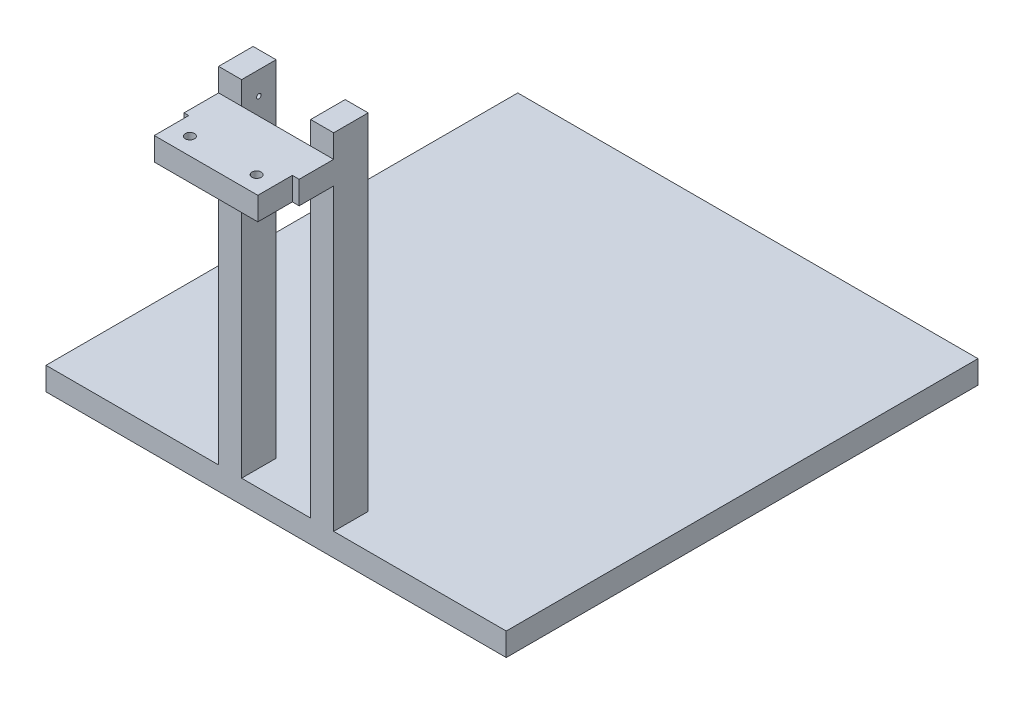
SolidWorks part; units mm, degrees
ref_plane "Front Plane" through (0, 0, 0) normal (0, 0, 1) x (1, 0, 0)
ref_plane "Top Plane" through (0, 0, 0) normal (0, 1, 0) x (1, 0, 0)
ref_plane "Right Plane" through (0, 0, 0) normal (1, 0, 0) x (0, 0, -1)
sketch "Sketch1" plane through (0, 0, 0) normal (0, 1, 0) x (1, 0, 0)
  line L1 (-100, 102.5) -> (100, 102.5)
  line L2 (-100, 102.5) -> (-100, -102.5)
  line L3 (-100, -102.5) -> (100, -102.5)
  line L4 (100, 102.5) -> (100, -102.5)
  line L5 (-100, 102.5) -> (100, -102.5) construction
  line L6 (-100, -102.5) -> (100, 102.5) construction
  point P0 (0, 0)
  dimension "D1" = 200
  dimension "D2" = 205
extrude "Boss-Extrude1" add sketch "Sketch1" along normal blind 10
sketch "Sketch2" plane through (0, 0, 0) normal (0, 1, 0) x (1, 0, 0)
  line L0 (0, -102.5) -> (0, 102.5)
  line L1 (-100, -102.5) -> (100, -102.5) construction
  line L2 (100, 102.5) -> (-100, 102.5) construction
  line L3 (0, 102.5) -> (66.3962, 67.7798)
  line L4 (-15, -102.5) -> (15, -102.5)
  line L5 (15, -102.5) -> (15, -87.5)
  line L6 (15, -87.5) -> (25, -87.5)
  line L7 (25, -87.5) -> (25, -102.5)
  line L8 (25, -102.5) -> (15, -102.5)
  line L9 (-15, -102.5) -> (-15, -87.5)
  line L10 (-15, -87.5) -> (-25, -87.5)
  line L11 (-25, -87.5) -> (-25, -102.5)
  line L12 (-25, -102.5) -> (-15, -102.5)
  line L13 (15, -102.5) -> (25, -102.5)
  line L14 (-25, -102.5) -> (-15, -102.5)
  point P10 (0, -102.5)
  dimension "D1" = 30
  dimension "D2" = 15
  dimension "D3" = 10
  dimension "D4" = 10
extrude "Boss-Extrude2" add sketch "Sketch2" along normal blind 160 contours L11 L12 L9 L10 | L8 L7 L6 L5
ref_plane "Plane1" through (0, 0, 102.5) normal (0, 0, 1) x (1, 0, 0)
sketch "Sketch4" plane through (0, 0, 102.5) normal (0, 0, 1) x (1, 0, 0)
  line L0 (-25, 160) -> (-25, 150)
  line L1 (-25, 160) -> (-25, 10) construction
  line L2 (-25, 150) -> (25, 150)
  line L3 (25, 160) -> (25, 10) construction
  line L4 (25, 150) -> (25, 160)
  line L5 (-25, 150) -> (25, 150)
  line L6 (-25, 150) -> (-25, 140)
  line L7 (-25, 140) -> (25, 140)
  line L8 (25, 140) -> (25, 150)
  point P13 (0, 150)
  dimension "D1" = 10
  dimension "D2" = 50
  dimension "D3" = 10
extrude "Boss-Extrude3" add sketch "Sketch4" along normal blind 15 contours L7 L8 L2 L6
ref_plane "Plane2" through (0, 0, 117.5) normal (0, 0, 1) x (1, 0, 0)
sketch "Sketch5" plane through (0, 0, 117.5) normal (0, 0, 1) x (1, 0, 0)
  line L0 (-22.9526, 150) -> (22.0474, 150)
  line L1 (-25, 150) -> (25, 150) construction
  line L2 (22.0474, 150) -> (22.0474, 140)
  line L3 (-25, 140) -> (25, 140) construction
  line L4 (22.0474, 140) -> (-22.9526, 140)
  line L5 (-22.9526, 140) -> (-22.9526, 150)
  point P5 (-0.4526, 150)
  dimension "D1" = 45
extrude "Boss-Extrude4" add sketch "Sketch5" along normal blind 15
ref_plane "Plane3" through (0, 150, 0) normal (0, 1, 0) x (1, 0, 0)
sketch "Sketch6" plane through (0, 150, 0) normal (0, 1, 0) x (1, 0, 0)
  circle A0 centre (-14.9526, -125) radius 2
  circle A1 centre (14.0474, -125) radius 2
extrude "Cut-Extrude1" cut sketch "Sketch6" against normal blind 15
ref_plane "Plane4" through (15, 0, 0) normal (1, 0, 0) x (0, 0, -1)
sketch "Sketch7" plane through (15, 0, 0) normal (1, 0, 0) x (0, 0, -1)
  line L0 (-95, 160) -> (-95, 150)
  line L1 (-102.5, 160) -> (-87.5, 160) construction
  circle A0 centre (-95, 150) radius 1
  dimension "D2" = 2
  dimension "D1" = 10
ref_plane "Plane5" through (0, 10, 0) normal (0, 1, 0) x (1, 0, 0)
sketch "Sketch9" plane through (15, 0, 0) normal (1, 0, 0) x (0, 0, -1)
ref_plane "Plane6" through (-15, 0, 0) normal (1, 0, 0) x (0, 0, -1)
sketch "Sketch10" plane through (-15, 0, 0) normal (1, 0, 0) x (0, 0, -1)
  line L0 (-95, 160) -> (-95, 150)
  line L1 (-102.5, 160) -> (-87.5, 160) construction
  circle A0 centre (-95, 150) radius 1
  dimension "D2" = 2
  dimension "D1" = 10
extrude "Cut-Extrude2" cut sketch "Sketch10" against normal blind 5
sketch "Sketch12" plane through (15, 0, 0) normal (1, 0, 0) x (0, 0, -1)
extrude "Cut-Extrude3" cut sketch "Sketch7" along normal blind 5
sketch "Sketch13" plane through (0, 10, 0) normal (0, 1, 0) x (1, 0, 0)
